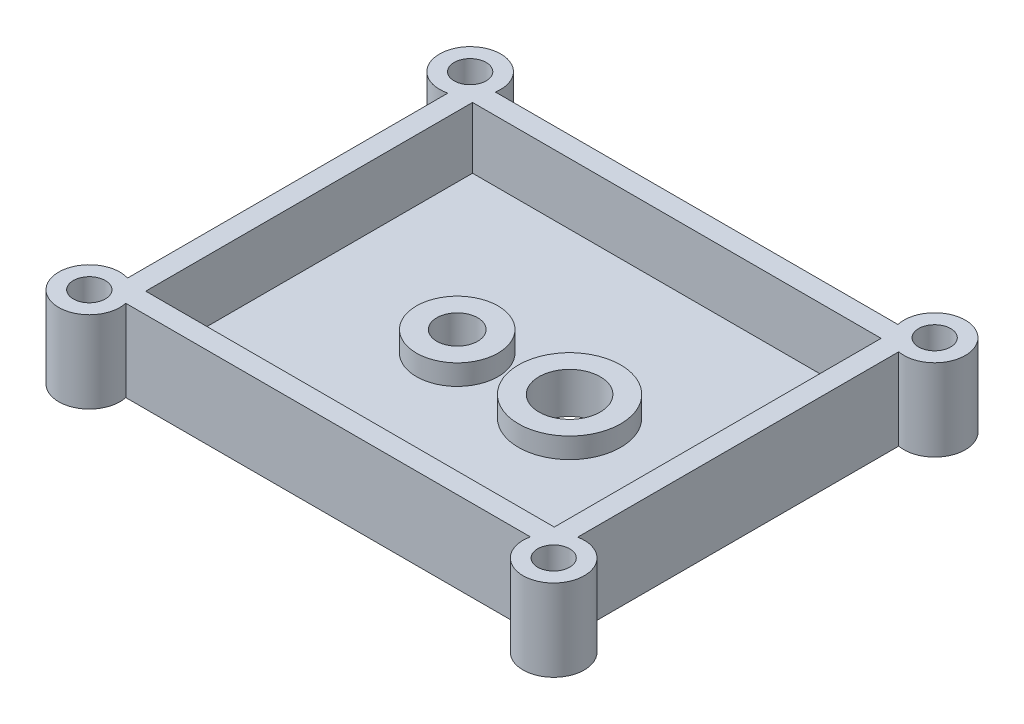
SolidWorks part; units mm, degrees
ref_plane "Front Plane" through (0, 0, 0) normal (0, 0, 1) x (1, 0, 0)
ref_plane "Top Plane" through (0, 0, 0) normal (0, 1, 0) x (1, 0, 0)
ref_plane "Right Plane" through (0, 0, 0) normal (1, 0, 0) x (0, 0, -1)
sketch "Sketch1" plane through (0, 0, 0) normal (0, 1, 0) x (1, 0, 0)
  line L1 (-34.925, -28.575) -> (34.925, -28.575)
  line L2 (-34.925, -28.575) -> (-34.925, 28.575)
  line L3 (-34.925, 28.575) -> (34.925, 28.575)
  line L4 (34.925, -28.575) -> (34.925, 28.575)
  line L5 (-34.925, -28.575) -> (34.925, 28.575) construction
  line L6 (-34.925, 28.575) -> (34.925, -28.575) construction
  point P0 (0, 0)
  dimension "D1" = 69.85
  dimension "D2" = 57.15
extrude "Boss-Extrude1" add sketch "Sketch1" along normal blind 12.7
sketch "Sketch2" plane through (0, 12.7, 0) normal (0, 1, 0) x (1, 0, 0)
  line L1 (-31.75, -25.4) -> (31.75, -25.4)
  line L2 (-31.75, -25.4) -> (-31.75, 25.4)
  line L3 (-31.75, 25.4) -> (31.75, 25.4)
  line L4 (31.75, -25.4) -> (31.75, 25.4)
  line L5 (-31.75, -25.4) -> (31.75, 25.4) construction
  line L6 (-31.75, 25.4) -> (31.75, -25.4) construction
  point P0 (0, 0)
  dimension "D1" = 63.5
  dimension "D2" = 50.8
extrude "Cut-Extrude1" cut sketch "Sketch2" against normal blind 9.525
sketch "Sketch3" plane through (0, 3.175, 0) normal (0, 1, 0) x (1, 0, 0)
  line L0 (0, 0) -> (0, -25.4) construction
  line L1 (-32.2754, 0) -> (31.75, 0) construction
  line L2 (31.75, -25.4) -> (31.75, 25.4) construction
  line L3 (0, 0) -> (0, 25.4) construction
  line L4 (31.75, 25.4) -> (-31.75, 25.4) construction
  line L5 (-31.75, -25.4) -> (31.75, -25.4) construction
  circle A0 centre (-8.7312, 0) radius 3.175
  circle A1 centre (8.7312, 0) radius 4.7625
  circle A2 centre (-8.7312, 0) radius 6.35
  circle A3 centre (8.7312, 0) radius 7.9375
  point P3 (-8.7312, 0)
  point P13 (8.7312, 0)
  dimension "D3" = 6.35
  dimension "D4" = 9.525
  dimension "D5" = 12.7
  dimension "D6" = 15.875
  dimension "D1" = 8.7312
  dimension "D2" = 8.7312
extrude "Boss-Extrude2" add sketch "Sketch3" along normal blind 3.175
sketch "Sketch5" plane through (0, 6.35, 0) normal (0, 1, 0) x (1, 0, 0)
  circle A0 centre (-8.7312, 0) radius 3.175
  dimension "D1" = 6.35
extrude "Cut-Extrude2" cut sketch "Sketch5" against normal through all
sketch "Sketch6" plane through (0, 6.35, 0) normal (0, 1, 0) x (1, 0, 0)
  circle A0 centre (8.7312, 0) radius 4.7625
  dimension "D1" = 9.525
extrude "Cut-Extrude3" cut sketch "Sketch6" against normal through all
sketch "Sketch8" plane through (0, 12.7, 0) normal (0, 1, 0) x (1, 0, 0)
  line L0 (-34.925, 28.575) -> (-34.925, -28.575) construction
  circle A0 centre (-36.0809, 29.3595) radius 4.7625
  circle A1 centre (35.8327, 29.637) radius 4.7625
  circle A2 centre (35.8648, -29.6086) radius 4.7625
  circle A3 centre (-36.322, -29.5906) radius 4.7625
  dimension "D1" = 9.525
  dimension "D2" = 1.397
  dimension "D3" = 1.397
  dimension "D4" = 1.397
  dimension "D5" = 1.397
extrude "Boss-Extrude3" add sketch "Sketch8" against normal blind 12.7
sketch "Sketch9" plane through (0, 12.7, 0) normal (0, 1, 0) x (1, 0, 0)
  circle A0 centre (-36.0809, 29.3595) radius 2.4892
  circle A1 centre (-36.322, -29.5906) radius 2.4892
  circle A2 centre (35.8648, -29.6086) radius 2.4892
  circle A3 centre (35.8327, 29.637) radius 2.4892
  dimension "D1" = 4.9784
extrude "Cut-Extrude4" cut sketch "Sketch9" against normal through all
